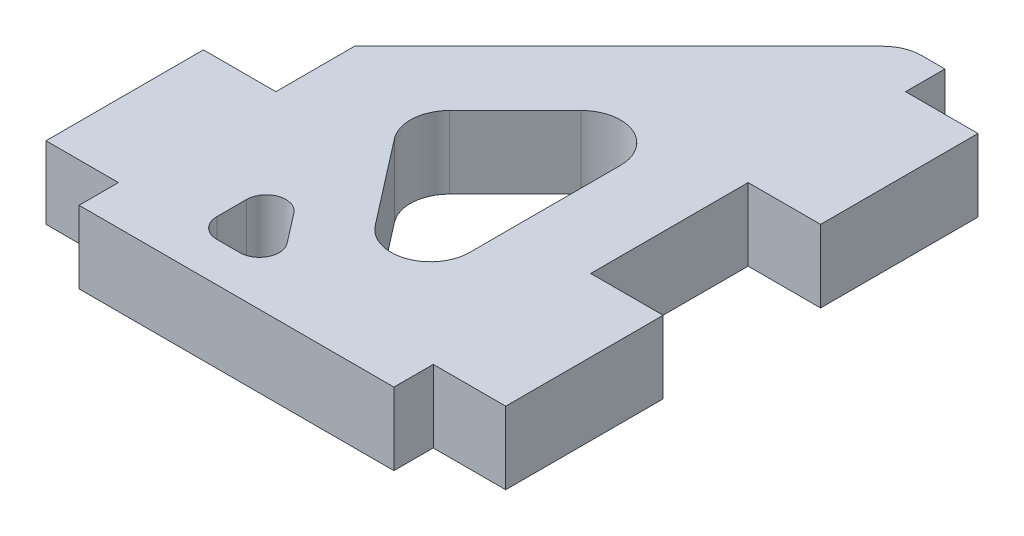
SolidWorks part; units mm, degrees
ref_plane "Front Plane" through (0, 0, 0) normal (0, 0, 1) x (1, 0, 0)
ref_plane "Top Plane" through (0, 0, 0) normal (0, 1, 0) x (1, 0, 0)
ref_plane "Right Plane" through (0, 0, 0) normal (1, 0, 0) x (0, 0, -1)
sketch "Sketch1" plane through (0, 0, 0) normal (0, 1, 0) x (1, 0, 0)
  line L0 (-9.525, -3.175) -> (15.875, -3.175) construction
  line L1 (15.875, -15.875) -> (-9.525, -15.875)
  line L2 (15.875, -15.875) -> (15.875, -9.525)
  line L3 (15.875, 3.175) -> (15.875, 15.875)
  line L4 (-9.525, -15.875) -> (-9.525, -9.525)
  line L5 (15.875, -15.875) -> (-9.525, 9.525) construction
  line L6 (15.875, 26.4583) -> (-9.525, -15.875) construction
  line L7 (-9.525, 3.175) -> (-9.525, 9.525)
  line L8 (-15.367, -9.525) -> (-9.525, -9.525)
  line L9 (-15.367, -9.525) -> (-15.367, 3.175)
  line L10 (-15.367, 3.175) -> (-9.525, 3.175)
  line L11 (3.175, 12.7) -> (3.175, -15.875) construction
  line L12 (-15.367, -9.525) -> (-9.525, 3.175) construction
  line L13 (-15.367, 3.175) -> (-9.525, -9.525) construction
  line L14 (21.717, 3.175) -> (15.875, -9.525) construction
  line L15 (21.717, -9.525) -> (15.875, 3.175) construction
  line L16 (21.717, 3.175) -> (15.875, 3.175)
  line L17 (21.717, -9.525) -> (21.717, 3.175)
  line L18 (21.717, -9.525) -> (15.875, -9.525)
  line L19 (21.717, 28.575) -> (15.875, 28.575)
  line L20 (21.717, 15.875) -> (21.717, 28.575)
  line L21 (21.717, 15.875) -> (15.875, 15.875)
  line L22 (-9.525, 22.225) -> (15.875, 22.225) construction
  line L23 (21.717, 28.575) -> (15.875, 15.875) construction
  line L24 (21.717, 15.875) -> (15.875, 28.575) construction
  line L25 (15.875, 28.575) -> (15.875, 31.75)
  line L26 (15.875, 31.75) -> (12.7, 31.75)
  line L27 (12.7, 31.75) -> (-9.525, 9.525)
  point P0 (0, 0)
  point P8 (-12.446, -3.175)
  point P19 (18.796, -3.175)
  point P27 (18.796, 22.225)
  dimension "D1" = 25.4
  dimension "D2" = 25.4
  dimension "D3" = 5.842
  dimension "D4" = 12.7
  dimension "D5" = 3.175
  dimension "D7" = 3.175
  dimension "D8" = 3.175
  dimension "D9" = 6.35
  dimension "D6" = 2
extrude "Boss-Extrude1" add sketch "Sketch1" along normal blind 5.842
sketch "Sketch2" plane through (0, 5.842, 0) normal (0, 1, 0) x (1, 0, 0)
  line L0 (-3.175, 6.8947) -> (9.525, 19.5947)
  line L1 (12.7, 31.75) -> (-9.525, 9.525) construction
  line L2 (9.525, 19.5947) -> (9.525, -9.525)
  line L3 (15.875, 3.175) -> (15.875, 15.875) construction
  line L4 (-3.175, 6.8947) -> (9.525, -9.525)
  line L5 (-9.525, 9.525) -> (-9.525, 3.175) construction
  line L6 (-9.525, -15.875) -> (15.875, -15.875) construction
  line L7 (-3.175, -0.8895) -> (3.5042, -9.525)
  line L8 (-3.175, -0.8895) -> (-3.175, -9.525)
  line L9 (-3.175, -9.525) -> (3.5042, -9.525)
  dimension "D1" = 6.35
  dimension "D2" = 6.35
  dimension "D3" = 6.35
  dimension "D4" = 6.35
  dimension "D5" = 6.35
  dimension "D6" = 6.35
  dimension "D7" = 4.7625
extrude "Cut-Extrude1" cut sketch "Sketch2" against normal through all
fillet "Fillet1" radius 3.175 1 edges at (12.7, 2.921, -31.75)
fillet "Fillet2" radius 1.5875 3 edges at (-3.175, 2.921, 0.8895) (-3.175, 2.921, 9.525) (3.5042, 2.921, 9.525)
fillet "Fillet3" radius 3.175 3 edges at (-3.175, 2.921, -6.8947) (9.525, 2.921, 9.525) (9.525, 2.921, -19.5947)
sketch "Sketch3" plane through (0, 5.842, 0) normal (0, 1, 0) x (1, 0, 0)
  line L0 (15.875, -15.875) -> (15.875, -9.525) construction
  line L1 (-9.525, -15.875) -> (15.875, -15.875)
  line L2 (-9.525, -15.875) -> (-9.525, -12.7)
  line L3 (-9.525, -12.7) -> (15.875, -12.7)
  line L4 (15.875, -15.875) -> (15.875, -12.7)
  dimension "D1" = 3.175
extrude "Cut-Extrude2" cut sketch "Sketch3" against normal through all
